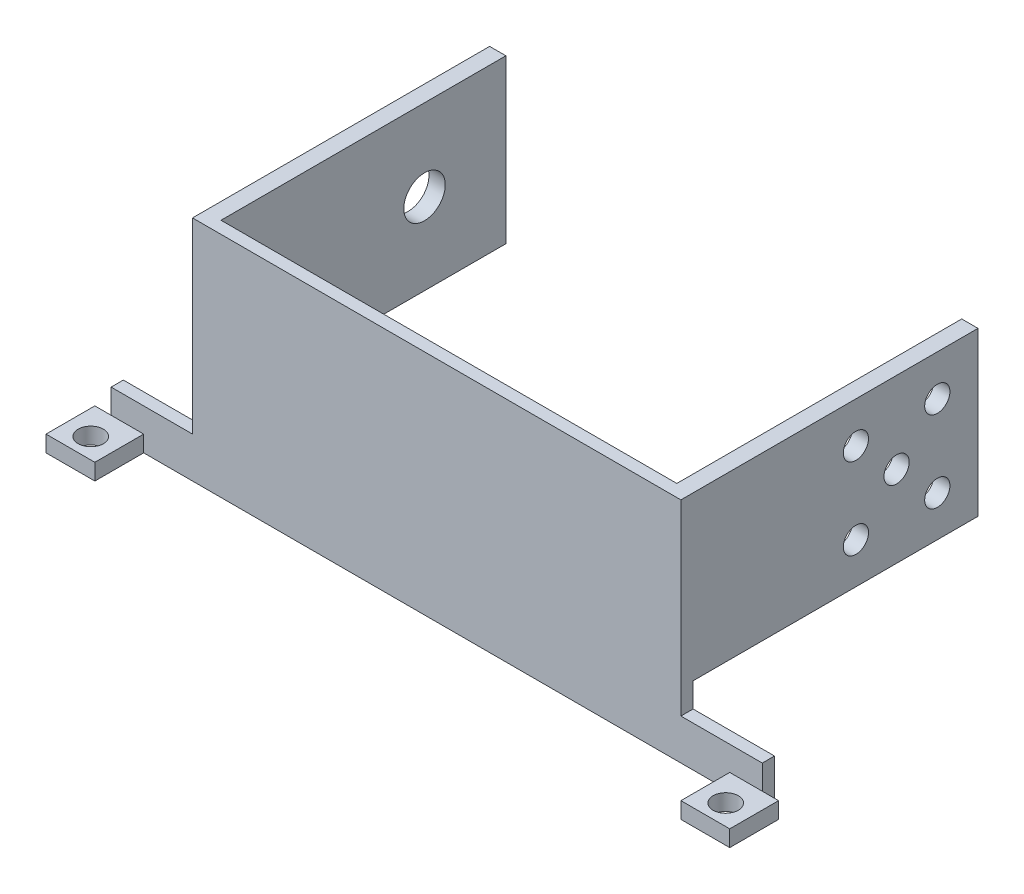
SolidWorks part; units mm, degrees
ref_plane "前视基准面" through (0, 0, 0) normal (0, 0, 1) x (1, 0, 0)
ref_plane "上视基准面" through (0, 0, 0) normal (0, 1, 0) x (1, 0, 0)
ref_plane "右视基准面" through (0, 0, 0) normal (1, 0, 0) x (0, 0, -1)
sketch "草图1" plane through (0, 0, 0) normal (0, 0, 1) x (1, 0, 0)
  line L2 (-30, 12) -> (-30, -12)
  line L3 (-30, -12) -> (30, -12)
  line L4 (30, 12) -> (30, -12)
  line L5 (-30, 12) -> (30, -12) construction
  line L6 (-30, -12) -> (30, 12) construction
  line L8 (-30, 12) -> (-30, 16)
  line L9 (-30, 16) -> (30, 16)
  line L10 (30, 12) -> (30, 16)
  point P0 (0, 0)
  dimension "D1" = 24
  dimension "D2" = 60
  dimension "D3" = 4
extrude "凸台-拉伸1" add sketch "草图1" along normal blind 1.5
sketch "草图2" plane through (0, 0, 1.5) normal (0, 0, 1) x (1, 0, 0)
  line L0 (-30, -12) -> (30, -12) construction
  line L1 (-40, -7) -> (-30, -7)
  line L3 (-40, -12) -> (-30, -12)
  line L6 (0, 0) -> (0, -12) construction
  line L7 (-30, 16) -> (-30, -12) construction
  line L14 (-27, -12) -> (-27, -7)
  line L15 (-30, -12) -> (30, -12) construction
  line L16 (-27, -12) -> (-30, -12)
  line L17 (-27, -7) -> (-30, -7)
  line L18 (-40, -7) -> (-40, -12)
  line L19 (40, -7) -> (40, -12)
  line L20 (40, -7) -> (30, -7)
  line L21 (27, -7) -> (30, -7)
  line L22 (27, -12) -> (27, -7)
  line L23 (27, -12) -> (30, -12)
  line L24 (40, -12) -> (30, -12)
  dimension "D3" = 3
  dimension "D5" = 10
extrude "凸台-拉伸2" add sketch "草图2" against normal blind 1.5
sketch "草图3" plane through (0, 0, 1.5) normal (0, 0, 1) x (1, 0, 0)
  line L0 (-40, -12) -> (40, -12) construction
  line L1 (36, -10) -> (42, -10)
  line L2 (36, -10) -> (36, -12)
  line L3 (36, -12) -> (42, -12)
  line L4 (42, -10) -> (42, -12)
  line L5 (0, 0) -> (0, 12) construction
  line L13 (-36, -12) -> (-42, -12)
  line L14 (-42, -10) -> (-42, -12)
  line L15 (-36, -10) -> (-42, -10)
  line L16 (-36, -10) -> (-36, -12)
  line L17 (-40, -7) -> (-40, -12) construction
  line L18 (40, -12) -> (40, -7) construction
  dimension "D1" = 2
  dimension "D2" = 6
  dimension "D3" = 4
  dimension "D4" = 4
extrude "凸台-拉伸3" add sketch "草图3" along normal blind 6
sketch "草图4" plane through (0, -12, 0) normal (0, -1, 0) x (1, 0, 0)
  line L0 (-36, 1.5) -> (36, 1.5) construction
  line L1 (0, 0) -> (0, 15.3913) construction
  circle A0 centre (39, 5) radius 1.55
  circle A1 centre (-39, 5) radius 1.55
  dimension "D1" = 3.5
  dimension "D3" = 3.1
  dimension "D2" = 39
sketch "草图5" plane through (0, 0, 0) normal (0, 0, -1) x (-1, 0, 0)
  line L0 (30, 16) -> (30, -7) construction
  line L1 (30, 16) -> (28, 16)
  line L2 (30, 16) -> (30, -4)
  line L3 (30, -4) -> (28, -4)
  line L4 (28, 16) -> (28, -4)
  line L5 (30, -7) -> (40, -7) construction
  line L6 (0, 0) -> (0, 16) construction
  line L8 (-30, -4) -> (-28, -4)
  line L9 (-28, 16) -> (-28, -4)
  line L10 (-30, 16) -> (-28, 16)
  line L11 (-30, 16) -> (-30, -4)
  dimension "D1" = 20
  dimension "D2" = 3
  dimension "D3" = 2
extrude "切除-拉伸1" cut sketch "草图4" against normal blind 4.5
extrude "凸台-拉伸4" add sketch "草图5" along normal blind 35
sketch "草图6" plane through (30, 0, 0) normal (1, 0, 0) x (0, 0, -1)
  line L0 (35, -4) -> (0, -4) construction
  line L4 (35, 16) -> (35, -4) construction
  line L5 (25, 6) -> (15, 6) construction
  line L6 (25, 6) -> (17.9289, 13.0711) construction
  line L7 (25, 6) -> (30, 11) construction
  circle A0 centre (25, 6) radius 1.55
  circle A1 centre (30, 11) radius 1.55
  circle A2 centre (25, 6) radius 9.9941 construction
  circle A3 centre (30, 1) radius 1.55
  circle A4 centre (20, 1) radius 1.55
  circle A5 centre (20, 11) radius 1.55
  dimension "D1" = 10
  dimension "D2" = 3.1
  dimension "D3" = 10
  dimension "D4" = 45
extrude "切除-拉伸2" cut sketch "草图6" against normal blind 35
sketch "草图7" plane through (-30, 0, 0) normal (-1, 0, 0) x (0, 0, 1)
  circle A2 centre (-25, 6) radius 2.55
  dimension "D1" = 5.1
extrude "切除-拉伸4" cut sketch "草图7" against normal blind 35
